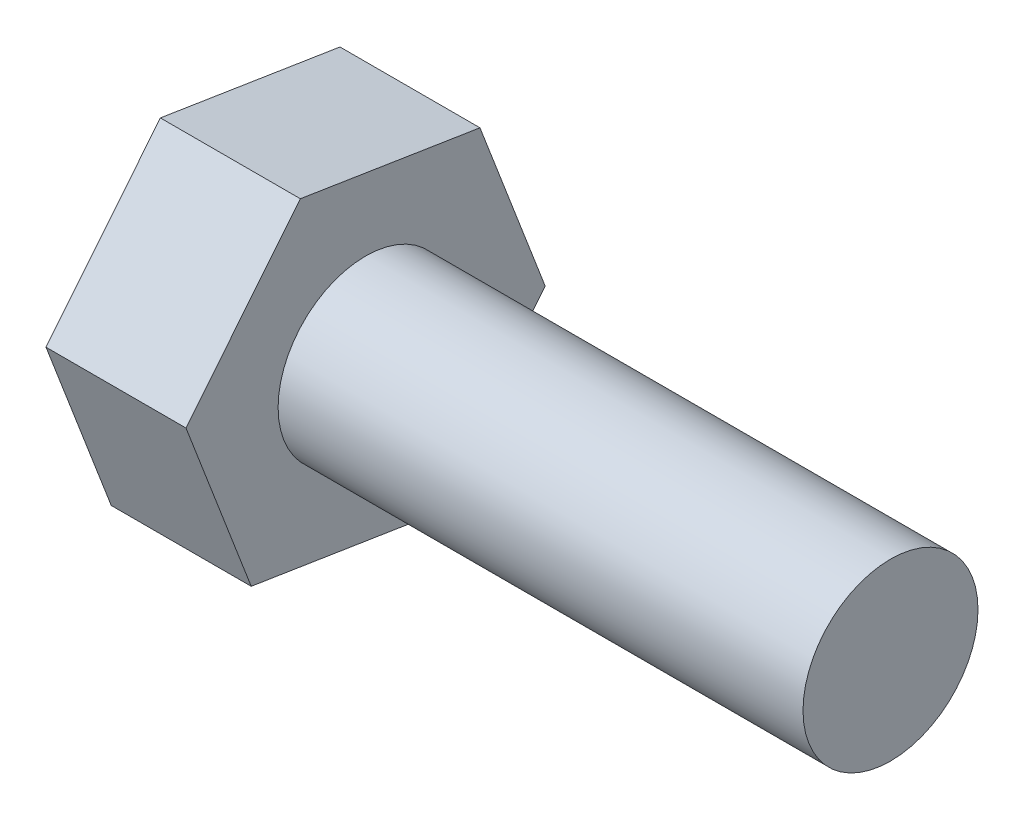
SolidWorks part; units mm, degrees
ref_plane "Спереди" through (0, 0, 0) normal (0, 0, 1) x (1, 0, 0)
ref_plane "Сверху" through (0, 0, 0) normal (0, 1, 0) x (1, 0, 0)
ref_plane "Справа" through (0, 0, 0) normal (1, 0, 0) x (0, 0, -1)
sketch "Эскиз1" plane through (0, 0, 0) normal (1, 0, 0) x (0, 0, -1)
  circle A0 centre (0, 0) radius 5
extrude "Вытянуть1" add sketch "Эскиз1" along normal blind 30
sketch "Эскиз2" plane through (0, 0, 0) normal (-1, 0, 0) x (0, 0, 1)
  line L1 (10.2652, 1.6207) -> (3.729, 9.7002)
  line L2 (3.729, 9.7002) -> (-6.5361, 8.0795)
  line L3 (-6.5361, 8.0795) -> (-10.2652, -1.6207)
  line L4 (-10.2652, -1.6207) -> (-3.729, -9.7002)
  line L5 (-3.729, -9.7002) -> (6.5361, -8.0795)
  line L6 (6.5361, -8.0795) -> (10.2652, 1.6207)
  circle A0 centre (0, 0) radius 9 construction
extrude "Вытянуть2" add sketch "Эскиз2" along normal blind 8
